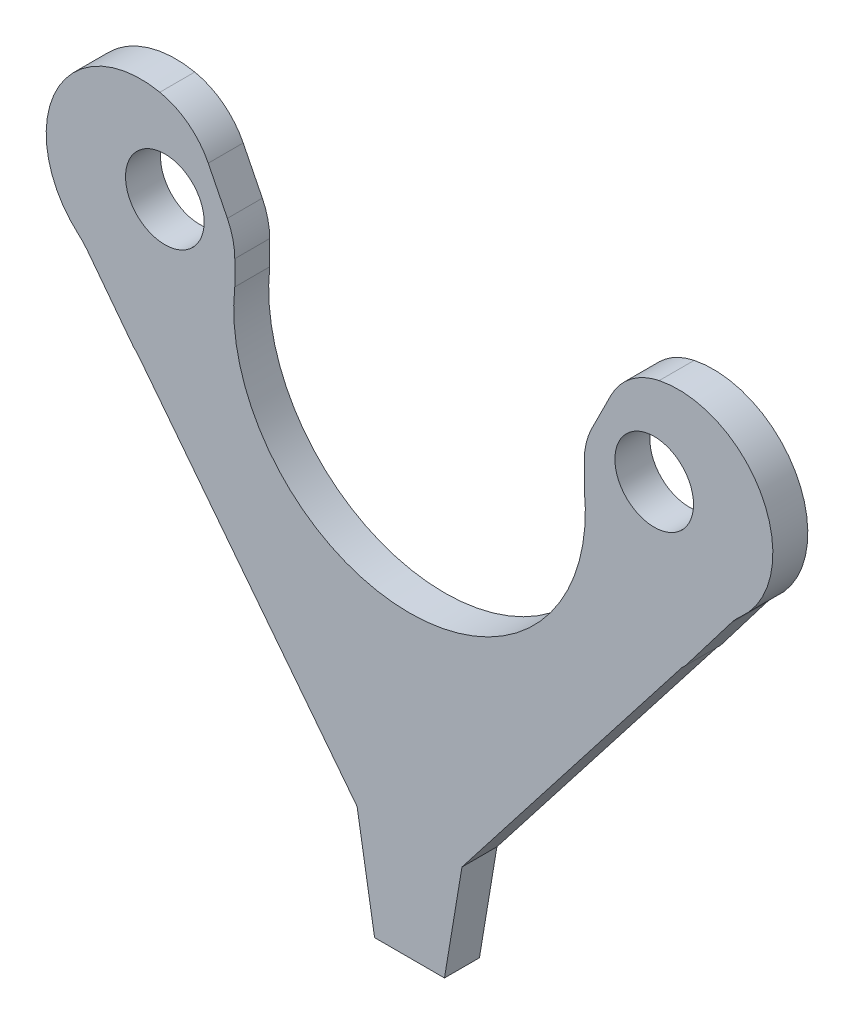
SolidWorks part; units mm, degrees
ref_plane "Front Plane" through (0, 0, 0) normal (0, 0, 1) x (1, 0, 0)
ref_plane "Top Plane" through (0, 0, 0) normal (0, 1, 0) x (1, 0, 0)
ref_plane "Right Plane" through (0, 0, 0) normal (1, 0, 0) x (0, 0, -1)
sketch "Sketch1" plane through (0, 0, 0) normal (0, 0, 1) x (1, 0, 0)
  line L4 (0, 0) -> (177.8, 0)
  line L13 (0, 0) -> (-50.8, 0)
  line L21 (25.4, -5.9961) -> (25.4, -14.879)
  line L22 (-28.0077, -30.3492) -> (-11.4236, -52.0764)
  line L23 (0, 0) -> (25.4, 0)
  line L24 (15.769, 19.262) -> (22.7185, 5.3631)
  line L25 (25.4, 0) -> (0, 0)
  line L26 (88.9, -118.0217) -> (88.9, 72.3175)
  line L29 (162.031, 19.262) -> (155.0815, 5.3631)
  line L30 (205.8077, -30.3492) -> (189.2236, -52.0764)
  line L31 (-11.4236, -52.0764) -> (25.4, -88.9)
  line L32 (25.4, -88.9) -> (152.4, -88.9)
  line L33 (70.9395, -70.9395) -> (32.8395, -32.8395)
  line L34 (189.2236, -52.0764) -> (152.4, -88.9)
  line L35 (106.8605, -70.9395) -> (144.9605, -32.8395)
  line L36 (152.4, -5.9961) -> (152.4, -14.879)
  line L42 (88.9, -118.0217) -> (63.5, -118.0217)
  line L43 (63.5, -118.0217) -> (114.3, -118.0217)
  line L44 (25.4, -88.9) -> (63.5, -118.0217)
  line L45 (114.3, -118.0217) -> (152.4, -88.9)
  line L46 (88.9, -118.0217) -> (88.9, -194.2217)
  line L47 (88.9, -194.2217) -> (76.2, -194.2217)
  line L48 (76.2, -194.2217) -> (101.6, -194.2217)
  line L49 (63.5, -118.0217) -> (76.2, -194.2217)
  line L50 (114.3, -118.0217) -> (101.6, -194.2217)
  line L51 (107.95, -156.1217) -> (152.4, -88.9)
  line L52 (25.4, -88.9) -> (69.85, -156.1217)
  arc A4 (106.8605, -70.9395) -> (70.9395, -70.9395) centre (88.9, -52.979) cw
  arc A5 (32.8395, -32.8395) -> (25.4, -14.879) centre (50.8, -14.879) cw
  arc A6 (144.9605, -32.8395) -> (152.4, -14.879) centre (127, -14.879) ccw
  arc A7 (25.4, -5.9961) -> (22.7185, 5.3631) centre (0, -5.9961) ccw
  arc A8 (152.4, -5.9961) -> (155.0815, 5.3631) centre (177.8, -5.9961) cw
  arc A9 (-31.4335, -26.6789) -> (-28.0077, -30.3492) centre (-48.1982, -45.7604) cw
  arc A10 (209.2335, -26.6789) -> (205.8077, -30.3492) centre (225.9982, -45.7604) ccw
  arc A11 (179.6222, 32.7799) -> (162.031, 19.262) centre (184.7495, 7.9028) ccw
  arc A12 (-1.8222, 32.7799) -> (15.769, 19.262) centre (-6.9495, 7.9028) cw
  circle A17 centre (0, 0) radius 14.2875
  circle A18 centre (177.8, 0) radius 14.2875
  arc A19 (-1.8222, 32.7799) -> (-31.4335, -26.6789) centre (-8.7574, -0.8691) ccw
  arc A20 (179.6222, 32.7799) -> (209.2335, -26.6789) centre (186.5574, -0.8691) cw
  point P5 (25.4, -25.4)
  point P11 (152.4, -25.4)
  point P30 (88.9, -88.9)
  point P36 (190.5, -50.8)
  point P42 (152.4, 0)
  point P48 (-50.8, 25.4)
  point P51 (-25.4, 50.8)
  point P57 (228.6, 25.4)
  point P60 (203.2, 50.8)
  point P63 (177.8, 50.8)
  point P66 (0, 50.8)
  dimension "D2" = 25.4
  dimension "D3" = 25.4
  dimension "D1" = 177.8
  dimension "D5" = 76.2
  dimension "D6" = 12.7
  dimension "D7" = 25.4
extrude "Boss-Extrude1" add sketch "Sketch1" along normal blind 12.7
sketch "Sketch2" plane through (0, 0, 0) normal (0, 0, -1) x (-1, 0, 0)
  line L0 (0, 0) -> (-177.8, 0)
  line L1 (-88.9, 0) -> (-88.9, -28.575)
  line L2 (-152.4, -14.879) -> (-25.4, -14.879)
  circle A0 centre (-88.9, -28.575) radius 57.15
  arc A1 (-152.4, -14.879) -> (-25.4, -14.879) centre (-88.9, -21.8441) ccw
extrude "Cut-Extrude1" cut sketch "Sketch2" against normal up to next contours A1 L2
sketch "Sketch3" plane through (0, 0, 0) normal (0, 0, -1) x (-1, 0, 0)
  line L0 (-205.8077, -30.3492) -> (-107.95, -156.1217)
  line L1 (-107.95, -156.1217) -> (-69.85, -156.1217)
  line L2 (-69.85, -156.1217) -> (28.0077, -30.3492)
  line L4 (-205.8077, -30.3492) -> (-152.7809, -21.8441)
  line L5 (-25.0191, -21.8441) -> (28.0077, -30.3492)
  arc A0 (-152.7809, -21.8441) -> (-25.0191, -21.8441) centre (-88.9, -21.8441) ccw
  arc A1 (-152.4, -14.879) -> (-25.4, -14.879) centre (-88.9, -21.8441) ccw construction
extrude "Boss-Extrude2" add sketch "Sketch3" against normal through all
